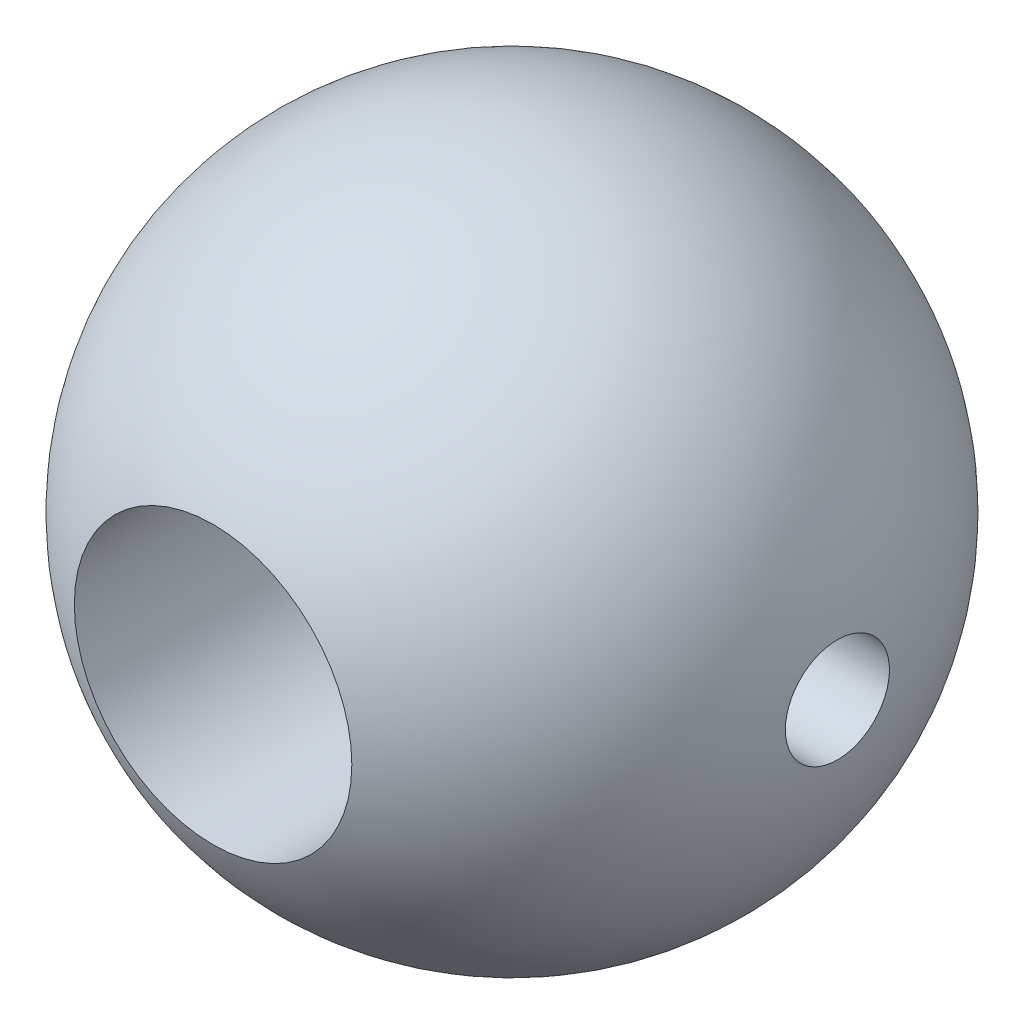
SolidWorks part; units mm, degrees
ref_plane "Front Plane" through (0, 0, 0) normal (0, 0, 1) x (1, 0, 0)
ref_plane "Top Plane" through (0, 0, 0) normal (0, 1, 0) x (1, 0, 0)
ref_plane "Right Plane" through (0, 0, 0) normal (1, 0, 0) x (0, 0, -1)
sketch "Sketch1" plane through (0, 0, 0) normal (0, 1, 0) x (1, 0, 0)
  line L0 (0, 0) -> (0, -8.7547) construction
  line L2 (4.064, 8.7547) -> (4.064, -8.7547)
  arc A1 (4.064, 8.7547) -> (4.064, -8.7547) centre (0, 0) cw
  point P6 (0, 0)
  point P10 (4.064, 0)
revolve "Revolve1" add sketch "Sketch1" angle 360 about L0
sketch "Sketch2" plane through (0, 0, 0) normal (0, 1, 0) x (1, 0, 0)
  line L1 (-11.888, 0) -> (13.9855, 0)
  line L2 (-11.888, 0) -> (-11.888, 1.524)
  line L3 (-11.888, 1.524) -> (13.9855, 1.524)
  line L4 (13.9855, 0) -> (13.9855, 1.524)
  dimension "D1" = 1.524
revolve "Cut-Revolve1" cut sketch "Sketch2" angle 360 about L1
